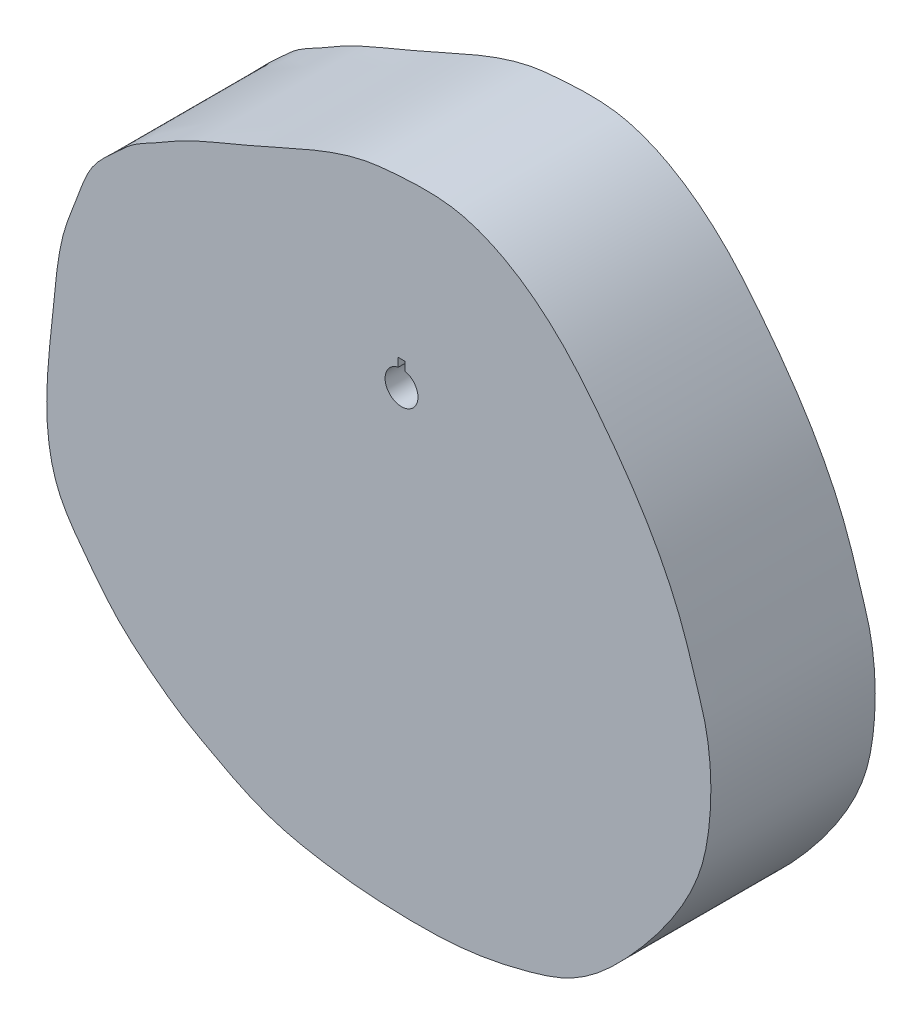
SolidWorks part; units mm, degrees
ref_plane "前视基准面" through (0, 0, 0) normal (0, 0, 1) x (1, 0, 0)
ref_plane "上视基准面" through (0, 0, 0) normal (0, 1, 0) x (1, 0, 0)
ref_plane "右视基准面" through (0, 0, 0) normal (1, 0, 0) x (0, 0, -1)
sketch "Model" plane through (0, 0, 0) normal (0, 0, 1) x (1, 0, 0)
  line L0 (55.5, 60.5) -> (61.5, 60.5)
  line L1 (58.9396, 62.6018) -> (59.9681, 60.5)
  line L2 (58.0604, 62.6018) -> (57.0319, 60.5)
  line L3 (47.721, 94.5) -> (47.721, 90.5)
  line L4 (47.721, 90.5) -> (46.221, 90.5)
  line L5 (47.721, 94.5) -> (46.221, 94.5)
  line L6 (49.25, 94.471) -> (49.25, 90.471)
  line L7 (49.25, 90.471) -> (50.75, 90.471)
  line L8 (49.25, 94.471) -> (50.75, 94.471)
  line L9 (55.5, 60.2451) -> (55.7549, 60.5)
  line L10 (55.5, 59.1225) -> (56.8775, 60.5)
  line L11 (56.5, 59) -> (58, 60.5)
  line L12 (57.6225, 59) -> (59.1225, 60.5)
  line L13 (58.7451, 59) -> (60.2451, 60.5)
  line L14 (59.8676, 59) -> (61.3676, 60.5)
  line L15 (58.5, 63.5) -> (58.5, 65)
  line L16 (58.5, 65) -> (58.3, 65)
  line L17 (58.5, 65) -> (58.7, 65)
  line L18 (58.3, 65) -> (58.3, 64.4798)
  line L19 (58.7, 65) -> (58.7129, 64.4771)
  line L25 (48.5, 77.2228) -> (48.5, 100.25)
  line L26 (48.5, 100.25) -> (48, 100.25)
  line L27 (48.5, 100.25) -> (49, 100.25)
  line L28 (48, 100.25) -> (48, 80.6949)
  line L29 (49, 100.25) -> (49, 80.6949)
  line L30 (46.221, 94.5) -> (46.221, 90.5)
  line L31 (50.75, 94.471) -> (50.75, 90.471)
  circle A0 centre (58.5, 63.5) radius 1
  circle A1 centre (48.5, 76.2228) radius 4.5
  circle A2 centre (48.5, 76.2228) radius 1
  arc A3 (61.3186, 67.1476) -> (54.527, 65.8378) centre (58.5, 63.5) ccw
  arc A4 (55.8645, 67.2821) -> (54.527, 65.8378) centre (58.5, 63.5) ccw
  spline S0 degree 3 poles (49.4415, 71.7131) (51.6017, 72.6799) (53.7696, 73.6565) (56.1979, 74.4106) (58.2935, 74.6044) (60.0662, 74.6931) (62.0608, 74.5414) (64.1263, 73.8343) (66.3492, 72.4904) (68.476, 70.6161) (70.7592, 67.8436) (73.3603, 64.2575) (75.4595, 60.179) (76.3571, 57.1264) (77.0029, 55.0611) (77.357, 53.0177) (77.3349, 50.2854) (76.8222, 47.0302) (75.092, 43.7173) (72.6547, 40.6943) (70.4241, 38.5028) (68.3165, 37.2174) (66.2389, 36.5727) (63.9626, 36.0368) (61.3675, 35.7019) (58.7262, 35.6854) (56.0679, 35.8111) (53.5442, 36.1375) (51.1189, 36.5946) (48.8133, 37.505) (46.9759, 38.5051) (45.2338, 39.4393) (43.2774, 40.8418) (41.1399, 42.5961) (39.299, 45.0338) (37.2995, 47.6516) (36.7666, 51.3901) (37.0753, 54.9299) (37.4291, 58.3266) (37.7409, 61.1761) (38.8007, 63.6679) (39.4994, 65.7961) (40.9753, 67.0731) (42.1517, 68.2176) (43.5098, 68.8791) (45.2242, 69.9431) (47.3824, 70.8562) (49.4415, 71.7131) (51.6017, 72.6799) (53.7696, 73.6565) knots -0.053528 -0.030186 -0.010705 0 0.026546 0.046329 0.060553 0.076868 0.088874 0.108295 0.128518 0.150854 0.175898 0.214483 0.256993 0.284989 0.290659 0.308876 0.334401 0.35592 0.38726 0.422471 0.449005 0.461679 0.481274 0.500786 0.517775 0.543869 0.564008 0.581536 0.604881 0.622946 0.640688 0.655045 0.670269 0.698381 0.72078 0.743531 0.77623 0.807771 0.829063 0.85826 0.875615 0.89409 0.910614 0.921398 0.933329 0.946472 0.969814 0.989295 1 1.026546 1.046329 1.060553 only from (50.9983, 72.4102) to (50.9983, 72.4102)
  spline S1 degree 3 poles (64.8504, 31.6645) (64.4791, 31.5954) (64.1033, 31.5336) (63.3516, 31.4265) (62.9745, 31.3809) (62.2379, 31.3079) (61.8775, 31.2797) (61.1689, 31.2378) (60.8191, 31.2237) (59.7844, 31.1975) (59.1138, 31.2014) (58.1904, 31.222) (57.9175, 31.23) (57.3643, 31.2508) (56.7477, 31.2793) (56.1191, 31.3228) (55.5183, 31.3735) (55.2636, 31.398) (54.7608, 31.4518) (54.2364, 31.5135) (53.7208, 31.5846) (53.1733, 31.665) (52.8979, 31.7077) (52.3272, 31.8027) (52.0349, 31.8548) (51.139, 32.0299) (50.5158, 32.1719) (49.6391, 32.4236) (49.403, 32.4965) (48.9414, 32.6491) (48.7139, 32.7293) (48.0414, 32.9802) (47.6063, 33.161) (46.9655, 33.4506) (46.75, 33.5524) (46.3357, 33.7549) (46.1357, 33.856) (45.5555, 34.1556) (45.1948, 34.3503) (44.7377, 34.5972) (44.6225, 34.6593) (44.3789, 34.7909) (44.2529, 34.8592) (43.8628, 35.0731) (43.5867, 35.2274) (43.0446, 35.5473) (42.7773, 35.7129) (42.2759, 36.0404) (42.0363, 36.2046) (41.5677, 36.5362) (41.3396, 36.7034) (41.0018, 36.9561) (40.8852, 37.0441) (40.6481, 37.2252) (40.2899, 37.502) (39.9255, 37.7951) (39.1925, 38.407) (38.6978, 38.8491) (38.0551, 39.4916) (37.9002, 39.6518) (37.5961, 39.9788) (37.4506, 40.1412) (37.0318, 40.6233) (36.7759, 40.9373) (36.3062, 41.5318) (36.0914, 41.8131) (35.8314, 42.155) (35.7753, 42.2289) (35.6097, 42.447) (35.4922, 42.6015) (35.1362, 43.0766) (34.8828, 43.4228) (34.3612, 44.2056) (34.0927, 44.6429) (33.7241, 45.3604) (33.6115, 45.5984) (33.4092, 46.0686) (33.3175, 46.3033) (33.0684, 47.004) (32.9365, 47.4662) (32.6041, 48.8928) (32.4967, 49.824) (32.4216, 51.1667) (32.4125, 51.6185) (32.4171, 52.4998) (32.431, 52.928) (32.4788, 53.8626) (32.5167, 54.362) (32.5857, 55.1557) (32.6147, 55.461) (32.7014, 56.3534) (32.7614, 56.9434) (32.8541, 57.8323) (32.8856, 58.1311) (32.9424, 58.6648) (32.9682, 58.9071) (33.0254, 59.4135) (33.0568, 59.6762) (33.1654, 60.4916) (33.2567, 61.0717) (33.4399, 61.9233) (33.5298, 62.3035) (33.6387, 62.6941) (33.7149, 62.9521) (33.751, 63.0687) (33.8232, 63.2929) (33.8596, 63.4016) (33.9687, 63.7181) (34.0412, 63.916) (34.1761, 64.2741) (34.2388, 64.4361) (34.3439, 64.706) (34.3877, 64.818) (34.5116, 65.1372) (34.5768, 65.3111) (34.7515, 65.7829) (34.855, 66.0635) (35.1189, 66.7048) (35.2793, 67.0662) (35.5751, 67.6172) (35.6681, 67.7801) (35.8329, 68.047) (35.8984, 68.1485) (36.026, 68.337) (36.0863, 68.4225) (36.2056, 68.5856) (36.2653, 68.6642) (36.4436, 68.8917) (36.5615, 69.0322) (36.9066, 69.4242) (37.1251, 69.6465) (37.5211, 70.0324) (37.6989, 70.1962) (37.9067, 70.3875) (37.9588, 70.4354) (38.0554, 70.5246) (38.0979, 70.5641) (38.2517, 70.7077) (38.3769, 70.8255) (38.6267, 71.0525) (38.7385, 71.1522) (39.0256, 71.397) (39.2099, 71.5468) (39.5114, 71.7699) (39.6095, 71.8395) (39.7962, 71.9669) (39.8869, 72.0263) (40.1499, 72.1931) (40.3131, 72.2893) (40.6483, 72.48) (40.8124, 72.5681) (41.0525, 72.6966) (41.1403, 72.7433) (41.2636, 72.81) (41.3046, 72.8325) (41.3943, 72.8824) (41.4412, 72.9088) (41.5882, 72.9926) (41.6945, 73.0543) (42.0399, 73.2555) (42.305, 73.4116) (42.7139, 73.6381) (42.8223, 73.6969) (43.0343, 73.8092) (43.3502, 73.9731) (43.6594, 74.124) (44.2673, 74.4115) (44.6585, 74.5842) (45.2838, 74.8527) (45.5275, 74.9552) (46.2322, 75.2507) (46.6892, 75.4413) (47.3944, 75.7404) (47.6495, 75.8496) (48.0866, 76.0398) (48.273, 76.1219) (48.6901, 76.3071) (48.9208, 76.4105) (49.156, 76.5158) knots 124.95846 124.95846 124.95846 124.95846 126.851625 126.851625 128.74479 128.74479 130.540216 130.540216 132.335642 132.335642 135.926493 135.926493 137.432557 137.432557 138.93862 140.758492 140.758492 142.085094 142.085094 143.411695 144.875502 144.875502 146.401689 146.401689 147.927876 147.927876 150.98025 150.98025 152.088003 152.088003 153.195757 153.195757 155.411264 155.411264 156.557338 156.557338 157.703412 157.703412 159.995561 159.995561 160.80138 160.80138 161.607198 161.607198 163.218836 163.218836 164.626323 164.626323 166.03381 166.03381 167.493852 167.493852 168.286348 168.286348 169.078843 170.663834 170.663834 173.833815 173.833815 174.840372 174.840372 175.846929 175.846929 177.860043 177.860043 179.81116 179.81116 180.359658 180.359658 181.456653 181.456653 183.521816 183.521816 185.586979 185.586979 186.519725 186.519725 187.45247 187.45247 189.317962 189.317962 193.324578 193.324578 195.476707 195.476707 197.628836 197.628836 200.317475 200.317475 202.071935 202.071935 205.580854 205.580854 207.361877 207.361877 208.763109 208.763109 210.164341 210.164341 212.966804 212.966804 214.063329 214.67253 214.67253 215.180192 215.180192 215.687854 215.687854 216.703178 216.703178 217.644549 217.644549 218.372655 218.372655 219.828867 219.828867 221.285079 221.285079 222.741291 222.741291 223.326665 223.326665 223.678609 223.678609 223.974426 223.974426 224.270244 224.270244 224.86188 224.86188 226.045151 226.045151 227.228422 227.228422 227.659654 227.659654 228.08589 228.08589 228.993858 228.993858 229.609088 229.609088 230.414166 230.414166 230.766752 230.766752 231.119337 231.119337 231.824508 231.824508 232.706509 232.706509 233.340309 233.340309 233.753263 233.753263 234.166216 234.166216 234.992124 234.992124 236.643938 236.643938 237.203236 237.203236 237.762535 238.881131 238.881131 241.118325 241.118325 242.624871 242.624871 245.637965 245.637965 247.38835 247.38835 248.685938 248.685938 250.231645 250.231645 250.231645 250.231645
  spline S2 degree 3 poles (49.156, 76.5158) (49.3963, 76.6239) (49.6421, 76.7344) (50.3969, 77.0701) (50.9236, 77.2998) (51.8444, 77.6749) (52.222, 77.8221) (53.0088, 78.108) (53.4229, 78.2483) (54.2714, 78.5017) (54.7035, 78.6159) (55.463, 78.7794) (55.7848, 78.8379) (56.3924, 78.9297) (56.6832, 78.9649) (57.2718, 79.0258) (57.5659, 79.0497) (57.9995, 79.0816) (58.1573, 79.0925) (58.4821, 79.1126) (58.6478, 79.1218) (59.155, 79.1454) (59.5064, 79.1557) (60.189, 79.1569) (60.5155, 79.1505) (61.13, 79.1183) (61.4106, 79.0969) (61.9027, 79.043) (62.1095, 79.0157) (62.4941, 78.9549) (62.6709, 78.923) (63.0166, 78.8528) (63.1872, 78.8144) (63.6915, 78.6902) (64.0182, 78.5953) (64.8242, 78.3302) (65.2905, 78.1468) (66.1486, 77.7641) (66.5455, 77.5661) (67.3155, 77.1446) (67.6873, 76.9216) (68.7649, 76.2233) (69.4322, 75.7201) (70.4456, 74.8602) (70.816, 74.5217) (71.4561, 73.8969) (71.7318, 73.6126) (72.2564, 73.0465) (72.5066, 72.7636) (73.0053, 72.1804) (73.2522, 71.8805) (73.661, 71.3719) (73.8266, 71.1622) (74.1533, 70.744) (74.6419, 70.1109) (75.1244, 69.4594) (76.0759, 68.128) (76.6929, 67.2017) (77.8563, 65.2622) (78.4016, 64.2517) (79.1123, 62.7322) (79.3202, 62.257) (79.679, 61.3715) (79.8343, 60.9597) (80.1166, 60.1621) (80.2458, 59.773) (80.4569, 59.1149) (80.5974, 58.6648) (80.7301, 58.2327) (80.8472, 57.8511) (80.9077, 57.655) (81.0125, 57.3161) (81.0504, 57.1932) (81.1179, 56.9657) (81.1465, 56.8668) (81.2366, 56.5432) (81.2924, 56.3244) (81.4454, 55.6699) (81.528, 55.2366) (81.6988, 54.1304) (81.7629, 53.4665) (81.8287, 52.15) (81.8295, 51.4989) (81.7919, 50.5691) (81.7748, 50.283) (81.735, 49.7685) (81.7142, 49.5401) (81.6641, 49.0725) (81.635, 48.8351) (81.5325, 48.1123) (81.444, 47.6166) (81.2696, 46.8602) (81.2051, 46.608) (81.0806, 46.1707) (81.0244, 45.987) (80.9067, 45.6274) (80.845, 45.4502) (80.6521, 44.9267) (80.5133, 44.5883) (80.0738, 43.6038) (79.7501, 42.9882) (79.2305, 42.0974) (79.0447, 41.7965) (78.4808, 40.9226) (78.0869, 40.3639) (77.3871, 39.4406) (76.8226, 38.7339) (76.2394, 38.0632) (75.783, 37.5557) (75.6038, 37.3608) (75.2293, 36.9626) (75.0346, 36.7608) (74.4255, 36.1509) (73.9857, 35.7382) (73.1825, 35.0649) (72.8437, 34.8001) (72.2151, 34.353) (71.6839, 34.0001) (71.109, 33.6736) (70.6313, 33.4256) (70.4293, 33.3273) (70.0333, 33.1469) (69.8379, 33.0638) (69.262, 32.8328) (68.8915, 32.7029) (68.2831, 32.5071) (68.0368, 32.4336) (67.6598, 32.3259) (67.5232, 32.288) (67.255, 32.2151) (66.8503, 32.1074) (66.0153, 31.9003) (65.2954, 31.7474) (64.8504, 31.6645) knots 0.006287 0.006287 0.006287 0.006287 1.587442 1.587442 4.749752 4.749752 6.84188 6.84188 8.934008 8.934008 10.910356 10.910356 12.246423 12.246423 13.58249 13.58249 15.083565 15.083565 15.937851 15.937851 16.792137 16.792137 18.500708 18.500708 19.989565 19.989565 21.164064 21.164064 21.984167 21.984167 22.659467 22.659467 23.334768 23.334768 24.685369 24.685369 26.766115 26.766115 28.697415 28.697415 30.628714 30.628714 34.491313 34.491313 36.870126 36.870126 38.776962 38.776962 40.683798 40.683798 42.73982 42.73982 44.22523 44.22523 45.71064 48.681459 48.681459 54.623098 54.623098 60.564737 60.564737 63.20019 63.20019 65.391996 65.391996 67.583803 67.583803 69.209371 70.253118 70.253118 71.606825 71.606825 72.274834 72.274834 72.739414 72.739414 73.717089 73.717089 75.672437 75.672437 78.759863 78.759863 81.84729 81.84729 83.23248 83.23248 84.354978 84.354978 85.477476 85.477476 87.722471 87.722471 88.827498 88.827498 89.622298 89.622298 90.417099 90.417099 92.0067 92.0067 95.185902 95.185902 96.892902 96.892902 100.306902 100.306902 102.759993 104.930632 104.930632 106.339376 106.339376 107.74812 107.74812 110.565607 110.565607 112.427206 112.427206 113.81362 115.061892 115.061892 115.921993 115.921993 116.782095 116.782095 118.502298 118.502298 119.7428 119.7428 120.479533 120.479533 121.216266 122.689732 124.95846 124.95846 124.95846 124.95846
  text T0 "ω" font "TIMES NEW ROMAN" height 2.5
  text T1 "O" font "TIMES NEW ROMAN" height 2
  text T2 "B" font "TIMES NEW ROMAN" height 2
  dimension "D1" = 0.5
  dimension "D2" = 0.5
  dimension "D3" = 0.2
  dimension "D4" = 0.2
extrude "凸台-拉伸6" add sketch "Model" along normal blind 10
